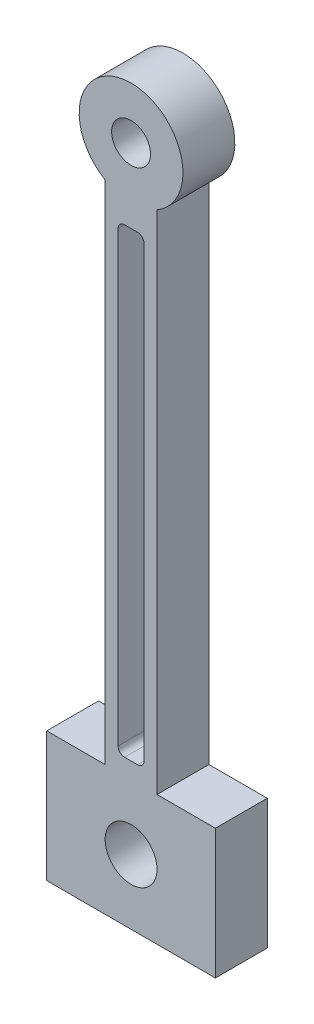
SolidWorks part; units mm, degrees
ref_plane "Front Plane" through (0, 0, 0) normal (0, 0, 1) x (1, 0, 0)
ref_plane "Top Plane" through (0, 0, 0) normal (0, 1, 0) x (1, 0, 0)
ref_plane "Right Plane" through (0, 0, 0) normal (1, 0, 0) x (0, 0, -1)
sketch "Sketch1" plane through (0, 0, 0) normal (0, 0, 1) x (1, 0, 0)
  line L0 (-13, -85) -> (-4, -85)
  line L2 (-4, -6.9282) -> (-4, -85)
  line L4 (4, -6.9282) -> (4, -85)
  line L5 (13, -85) -> (4, -85)
  line L6 (13, -85) -> (13, -105)
  line L7 (13, -105) -> (-13, -105)
  line L8 (-13, -85) -> (-13, -105)
  line L9 (13, -85) -> (-13, -105) construction
  line L10 (13, -105) -> (-13, -85) construction
  line L11 (4, -85) -> (13, -85)
  line L12 (4, -85) -> (13, -85)
  line L13 (-4, -85) -> (-13, -85)
  line L14 (-1, -11.431) -> (1, -11.431)
  line L15 (-2, -12.431) -> (-2, -81.5205)
  line L16 (-1, -82.5205) -> (1, -82.5205)
  line L17 (2, -12.431) -> (2, -81.5205)
  circle A0 centre (0, 0) radius 3
  circle A1 centre (0, 0) radius 5
  arc A2 (4, -6.9282) -> (-4, -6.9282) centre (0, 0) ccw
  circle A3 centre (0, -95) radius 4
  circle A4 centre (0, -95) radius 6
  arc A5 (-2, -81.5205) -> (-1, -82.5205) centre (-1, -81.5205) ccw
  arc A6 (1, -82.5205) -> (2, -81.5205) centre (1, -81.5205) ccw
  arc A7 (2, -12.431) -> (1, -11.431) centre (1, -12.431) ccw
  arc A8 (-2, -12.431) -> (-1, -11.431) centre (-1, -12.431) cw
  point P25 (2, -11.431)
  point P28 (-2, -11.431)
  dimension "D1" = 16
  dimension "D2" = 10
  dimension "D3" = 6
  dimension "D6" = 12
  dimension "D7" = 8
  dimension "D13" = 1
  dimension "D4" = 20
  dimension "D5" = 26
  dimension "D8" = 95
  dimension "D9" = 8
  dimension "D10" = 9
  dimension "D11" = 4
  dimension "D12" = 2
extrude "Boss-Extrude1" add sketch "Sketch1" along normal blind 8 contours L4 A2 L2 L0 L8 L7 L6 L5 A4 A1 L15 A8 L14 A7 L17 A6 L16 A5 | A1 A0 | A4 A3
